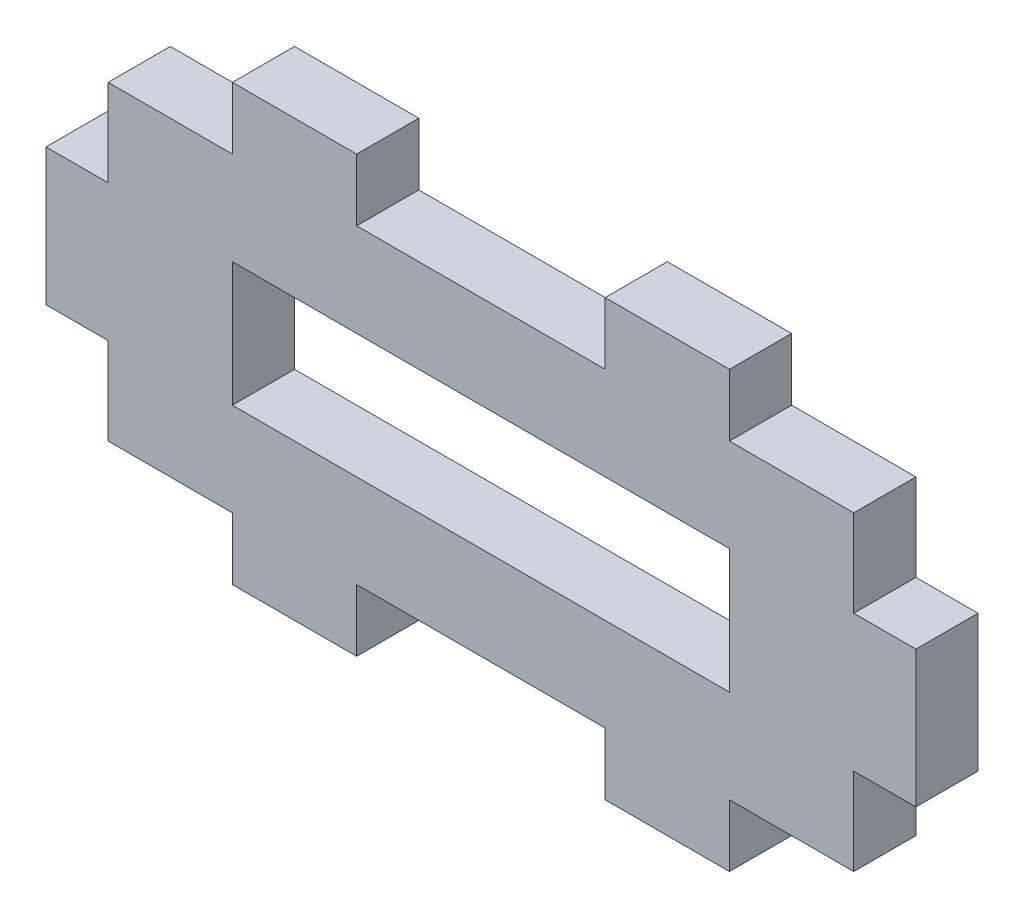
SolidWorks part; units mm, degrees
ref_plane "Front Plane" through (0, 0, 0) normal (0, 0, 1) x (1, 0, 0)
ref_plane "Top Plane" through (0, 0, 0) normal (0, 1, 0) x (1, 0, 0)
ref_plane "Right Plane" through (0, 0, 0) normal (1, 0, 0) x (0, 0, -1)
sketch "Sketch1" plane through (0, 0, 0) normal (0, 0, 1) x (1, 0, 0)
  line L0 (0, 0) -> (0, 16.6053) construction
  line L1 (-30, -12.5) -> (-20, -12.5)
  line L2 (-30, -12.5) -> (-30, -5.5)
  line L3 (-30, 12.5) -> (-20, 12.5)
  line L4 (30, -12.5) -> (30, -5.5)
  line L5 (-30, -12.5) -> (30, 12.5) construction
  line L6 (-30, 12.5) -> (30, -12.5) construction
  line L7 (-20, -5) -> (20, -5)
  line L8 (-20, -5) -> (-20, 5)
  line L9 (-20, 5) -> (20, 5)
  line L10 (20, -5) -> (20, 5)
  line L11 (-20, -5) -> (20, 5) construction
  line L12 (-20, 5) -> (20, -5) construction
  line L13 (-30, 5.5) -> (-35, 5.5)
  line L15 (-30, -5.5) -> (-35, -5.5)
  line L16 (-35, 5.5) -> (-35, -5.5)
  line L17 (-30, 5.5) -> (-30, 12.5)
  line L18 (-10, 12.5) -> (10, 12.5)
  line L20 (-20, 12.5) -> (-20, 17.5)
  line L21 (-20, 17.5) -> (-10, 17.5)
  line L22 (-10, 12.5) -> (-10, 17.5)
  line L23 (0, 0) -> (-29.0356, 0) construction
  line L24 (-20, -12.5) -> (-20, -17.5)
  line L25 (-20, -17.5) -> (-10, -17.5)
  line L26 (-10, -12.5) -> (-10, -17.5)
  line L27 (30, -5.5) -> (35, -5.5)
  line L28 (35, 5.5) -> (35, -5.5)
  line L29 (30, 5.5) -> (35, 5.5)
  line L30 (20, -12.5) -> (20, -17.5)
  line L31 (10, -12.5) -> (10, -17.5)
  line L32 (20, -17.5) -> (10, -17.5)
  line L33 (20, 12.5) -> (20, 17.5)
  line L34 (20, 17.5) -> (10, 17.5)
  line L35 (10, 12.5) -> (10, 17.5)
  line L36 (20, 12.5) -> (30, 12.5)
  line L37 (30, 5.5) -> (30, 12.5)
  line L38 (20, -12.5) -> (30, -12.5)
  line L39 (-10, -12.5) -> (10, -12.5)
  point P0 (0, 0)
  point P6 (0, 0)
  dimension "D1" = 60
  dimension "D2" = 25
  dimension "D3" = 40
  dimension "D4" = 10
  dimension "D5" = 5
  dimension "D6" = 11
  dimension "D7" = 7
  dimension "D8" = 5
  dimension "D9" = 10
  dimension "D10" = 10
extrude "Boss-Extrude1" add sketch "Sketch1" along normal blind 5
